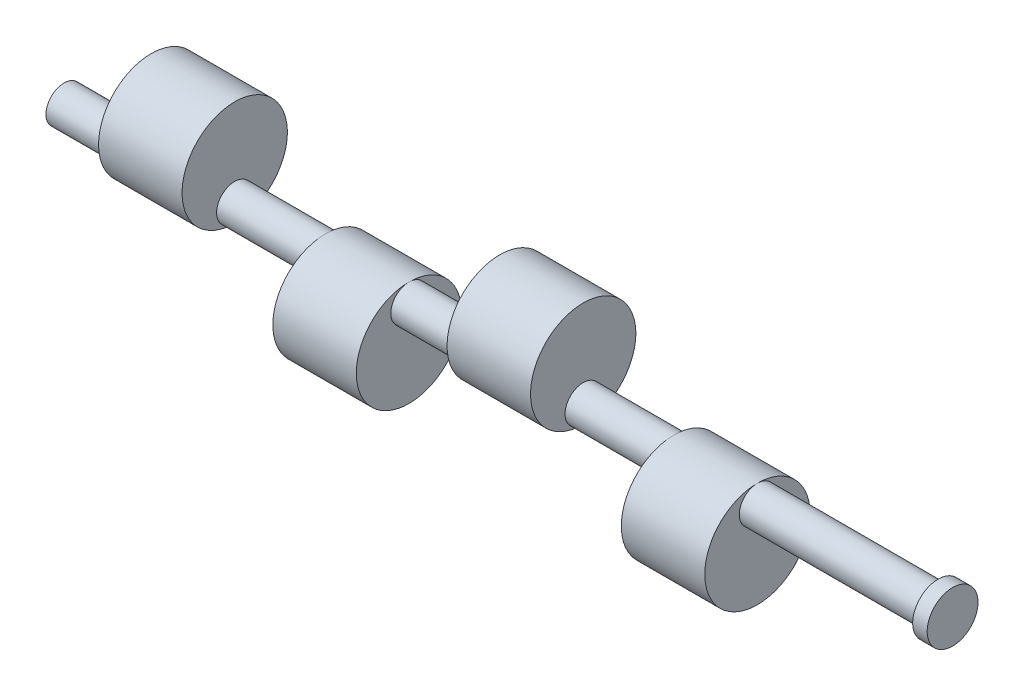
SolidWorks part; units mm, degrees
ref_plane "前基準面" through (0, 0, 0) normal (0, 0, 1) x (1, 0, 0)
ref_plane "上基準面" through (0, 0, 0) normal (0, 1, 0) x (1, 0, 0)
ref_plane "右基準面" through (0, 0, 0) normal (1, 0, 0) x (0, 0, -1)
sketch "草圖1" plane through (0, 0, 0) normal (0, 0, 1) x (1, 0, 0)
  line L0 (0, 0) -> (-33.7391, 0) construction
  line L2 (0, 0) -> (-264.89, 0)
  line L3 (0, 0) -> (0, 5)
  line L4 (0, 5) -> (-264.89, 5)
  line L5 (-264.89, 0) -> (-264.89, 5)
  dimension "D1" = 5
  dimension "D2" = 264.89
revolve "旋轉1" add sketch "草圖1" angle 360 about L0
ref_plane "平面1" through (-240.89, 0, 0) normal (-1, 0, 0) x (0, 0, 1)
sketch "草圖2" plane through (-240.89, 0, 0) normal (-1, 0, 0) x (0, 0, 1)
  line L0 (0, 0) -> (0, -5) construction
  circle A0 centre (0, 9.5) radius 14.5
  circle A1 centre (0, 0) radius 5 construction
  dimension "D1" = 24
extrude "填料-伸長1" add sketch "草圖2" against normal blind 23
ref_plane "平面2" through (-192.89, 0, 0) normal (-1, 0, 0) x (0, 0, 1)
sketch "草圖3" plane through (-192.89, 0, 0) normal (-1, 0, 0) x (0, 0, 1)
  circle A0 centre (0, -9.5) radius 14.5
  circle A1 centre (0, 0) radius 5 construction
  circle A2 centre (0, 9.5) radius 14.5 construction
extrude "填料-伸長2" add sketch "草圖3" against normal blind 23
ref_plane "平面3" through (-144.89, 0, 0) normal (-1, 0, 0) x (0, 0, 1)
sketch "草圖4" plane through (-144.89, 0, 0) normal (-1, 0, 0) x (0, 0, 1)
  circle A0 centre (0, 9.5) radius 14.5 construction
  circle A1 centre (0, 9.5) radius 14.5
extrude "填料-伸長3" add sketch "草圖4" against normal blind 23
ref_plane "平面4" through (-96.89, 0, 0) normal (-1, 0, 0) x (0, 0, 1)
sketch "草圖5" plane through (-96.89, 0, 0) normal (-1, 0, 0) x (0, 0, 1)
  circle A0 centre (0, -9.5) radius 14.5 construction
  circle A1 centre (0, -9.5) radius 14.5
extrude "填料-伸長4" add sketch "草圖5" against normal blind 23
sketch "草圖7" plane through (0, 0, 0) normal (1, 0, 0) x (0, 0, -1)
  circle A1 centre (0, 0) radius 5
  circle A2 centre (0, 0) radius 5
  dimension "D1" = 0
extrude "除料-伸長1" cut sketch "草圖7" against normal blind 20.12
sketch "草圖8" plane through (-20.12, 0, 0) normal (1, 0, 0) x (0, 0, -1)
  circle A0 centre (0, 0) radius 7
  dimension "D1" = 14
extrude "填料-伸長6" add sketch "草圖8" against normal blind 4
